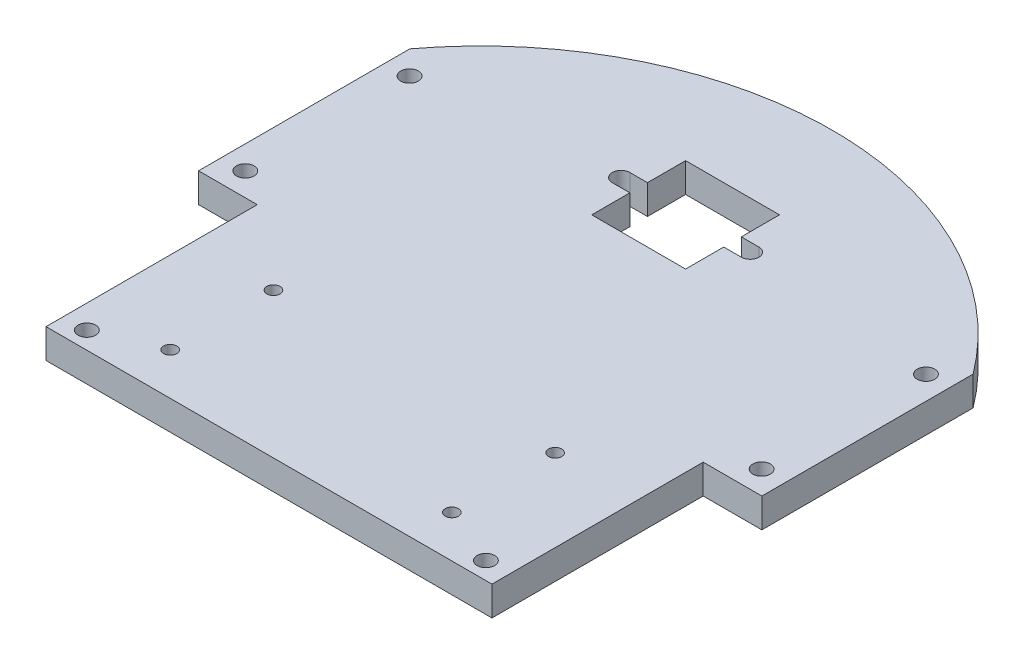
SolidWorks part; units mm, degrees
ref_plane "Front Plane" through (0, 0, 0) normal (0, 0, 1) x (1, 0, 0)
ref_plane "Top Plane" through (0, 0, 0) normal (0, 1, 0) x (1, 0, 0)
ref_plane "Right Plane" through (0, 0, 0) normal (1, 0, 0) x (0, 0, -1)
sketch "Sketch1" plane through (0, 0, 0) normal (0, 1, 0) x (1, 0, 0)
  line L0 (0, 92.8278) -> (0, -100.9894) construction
  line L1 (-116.4382, 0) -> (109.8492, 0) construction
  line L2 (-38, -51) -> (38, -51)
  line L3 (-38, -51) -> (-38, -15)
  line L4 (38, -51) -> (38, -15)
  line L5 (38, -15) -> (48, -15)
  line L6 (48, -15) -> (48, 21)
  line L7 (-38, -15) -> (-48, -15)
  line L8 (-48, -15) -> (-48, 21)
  line L9 (-8, 28) -> (8, 28)
  line L10 (8, 28) -> (8, 21.5)
  line L11 (8, 21.5) -> (11, 21.5)
  line L12 (-8, 28) -> (-8, 21.5)
  line L13 (11, 18.5) -> (8, 18.5)
  line L14 (8, 18.5) -> (8, 12)
  line L15 (8, 12) -> (-8, 12)
  line L16 (-8, 12) -> (-8, 18.5)
  line L17 (-8, 18.5) -> (-11, 18.5)
  line L18 (-8, 21.5) -> (-11, 21.5)
  arc A0 (-48, 21) -> (48, 21) centre (0, -15) cw
  circle A2 centre (34, -48.04) radius 1.5
  circle A11 centre (-34, -48.04) radius 1.5
  circle A12 centre (-44, -11.04) radius 1.5
  circle A13 centre (-44, 16.96) radius 1.5
  circle A14 centre (44, 16.96) radius 1.5
  circle A15 centre (44, -11.04) radius 1.5
  circle A16 centre (-24, -26.24) radius 1.125
  circle A17 centre (-24, -43.84) radius 1.125
  circle A18 centre (24, -26.24) radius 1.125
  circle A19 centre (24, -43.84) radius 1.125
  arc A20 (-11, 21.5) -> (-11, 18.5) centre (-11, 20) ccw
  arc A21 (11, 21.5) -> (11, 18.5) centre (11, 20) cw
  point P48 (0, 0)
  point P49 (0, 0)
  point P50 (0, 0)
  point P51 (0, 0)
  point P52 (0, 0)
  point P53 (0, 0)
  point P54 (11, 18.5)
  dimension "D9" = 60
  dimension "D10" = 3
  dimension "D11" = 3
  dimension "D12" = 3
  dimension "D13" = 3
  dimension "D14" = 3
  dimension "D15" = 3
  dimension "D16" = 2.25
  dimension "D17" = 2.25
  dimension "D18" = 2.25
  dimension "D19" = 2.25
  dimension "D24" = 1.5
  dimension "D25" = 1.5
  dimension "D1" = 76
  dimension "D2" = 38
  dimension "D3" = 36
  dimension "D4" = 36
  dimension "D5" = 10
  dimension "D6" = 36
  dimension "D7" = 10
  dimension "D8" = 15
  dimension "D20" = 16
  dimension "D21" = 16
  dimension "D22" = 8
  dimension "D23" = 6.5
  dimension "D26" = 6.5
  dimension "D27" = 6.5
  dimension "D28" = 3
  dimension "D29" = 3
  dimension "D30" = 20
  dimension "D31" = 4
  dimension "D32" = 2.96
  dimension "D33" = 4
  dimension "D34" = 2.96
  dimension "D35" = 4
  dimension "D36" = 3.96
  dimension "D37" = 4
  dimension "D38" = 3.96
  dimension "D39" = 4
  dimension "D40" = 4
  dimension "D41" = 28
  dimension "D42" = 28
  dimension "D43" = 7.16
  dimension "D44" = 14
  dimension "D45" = 14
  dimension "D46" = 24.76
extrude "Boss-Extrude1" add sketch "Sketch1" along normal blind 5
